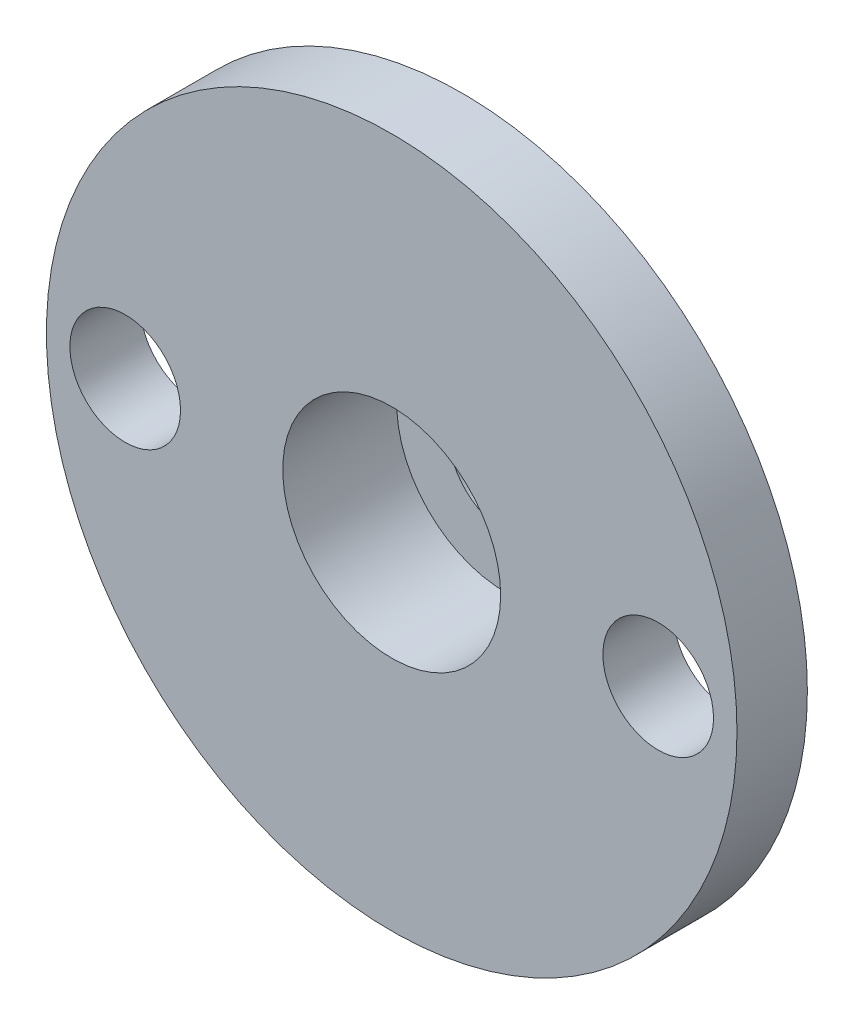
SolidWorks part; units mm, degrees
ref_plane "Plan de face" through (0, 0, 0) normal (0, 0, 1) x (1, 0, 0)
ref_plane "Plan de dessus" through (0, 0, 0) normal (0, 1, 0) x (1, 0, 0)
ref_plane "Plan de droite" through (0, 0, 0) normal (1, 0, 0) x (0, 0, -1)
sketch "Esquisse1" plane through (0, 0, 0) normal (0, 0, 1) x (1, 0, 0)
  circle A0 centre (0, 0) radius 10.3
  dimension "D1" = 20.6
extrude "Boss.-Extru.1" add sketch "Esquisse1" along normal blind 2.1
sketch "Esquisse2" plane through (0, 0, 0) normal (0, 0, 1) x (1, 0, 0)
  circle A0 centre (0, 0) radius 4.8
  dimension "D1" = 9.6
extrude "Boss.-Extru.2" add sketch "Esquisse2" against normal blind 3.3
sketch "Esquisse3" plane through (0, 0, 2.1) normal (0, 0, 1) x (1, 0, 0)
  circle A0 centre (0, 0) radius 7.95 construction
  circle A1 centre (7.95, 0) radius 1.65
  circle A2 centre (-7.95, 0) radius 1.65
  circle A3 centre (0, 0) radius 6.3 construction
  dimension "D1" = 12.6
  dimension "D2" = 3.3
  dimension "D3" = 3.3
extrude "Enlèv. mat.-Extru.1" cut sketch "Esquisse3" against normal through all
hole_wizard "Chambrage pour vis à six pans creux M31" positions "Esquisse3D1" profile "Esquisse4" counterbore size "M3" standard "ISO" end condition through all
sketch3d "Esquisse3D1"
  point P0 (0, 0, 0)
  point P3 (0, 0, 0)
  point P5 (0, 0, 2.1)
  point P8 (0, 0, 0)
sketch "Esquisse4" plane through (0, 0, 2.1) normal (1, 0, 0) x (0, -1, 0)
  line L0 (0, 0) -> (0, 5.4)
  line L1 (0, 5.4) -> (1.7, 5.4)
  line L3 (1.7, 5.4) -> (1.7, 3.4)
  line L4 (1.7, 3.4) -> (3.25, 3.4)
  line L5 (3.25, 3.4) -> (3.25, 0)
  line L7 (3.25, 0) -> (0, 0)
  line L11 (0, -6.35) -> (0, 107.95) construction
  dimension "Diamètre du perçage jusqu'au prochain" = 3.4
  dimension "Profondeur du perçage jusqu'au prochain" = 5.4
  dimension "Diamètre du chambrage" = 6.5
  dimension "Profondeur du chambrage" = 3.4
